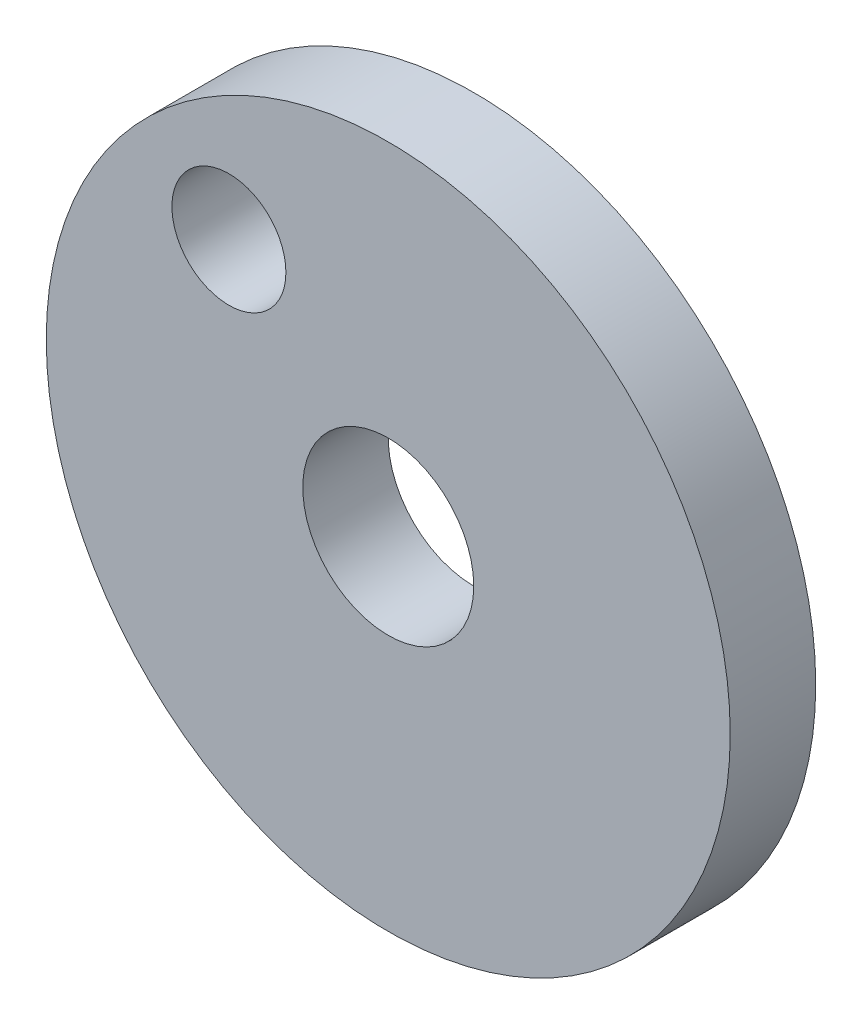
SolidWorks part; units mm, degrees
ref_plane "Front Plane" through (0, 0, 0) normal (0, 0, 1) x (1, 0, 0)
ref_plane "Top Plane" through (0, 0, 0) normal (0, 1, 0) x (1, 0, 0)
ref_plane "Right Plane" through (0, 0, 0) normal (1, 0, 0) x (0, 0, -1)
sketch "Sketch1" plane through (0, 0, 0) normal (0, 0, 1) x (1, 0, 0)
  circle A0 centre (0, 0) radius 60
  point P2 (0, 0)
extrude "Boss-Extrude1" add sketch "Sketch1" along normal blind 15
sketch "Sketch2" plane through (0, 0, 0) normal (0, 0, 1) x (1, 0, 0)
  circle A0 centre (0, 0) radius 60
  point P2 (0, 0)
sketch "Sketch3" plane through (0, 0, 15) normal (0, 0, 1) x (1, 0, 0)
  circle A0 centre (0, 0) radius 15
  point P2 (0, 0)
  point P3 (0, 0)
extrude "Cut-Extrude1" cut sketch "Sketch3" against normal blind 15 contours A0
sketch "Sketch4" plane through (0, 0, 15) normal (0, 0, 1) x (1, 0, 0)
  circle A0 centre (-27.9556, 31.1813) radius 10
  point P2 (-28.9481, 30.3542)
  point P3 (-27.9556, 31.1813)
extrude "Cut-Extrude2" cut sketch "Sketch4" against normal blind 15
